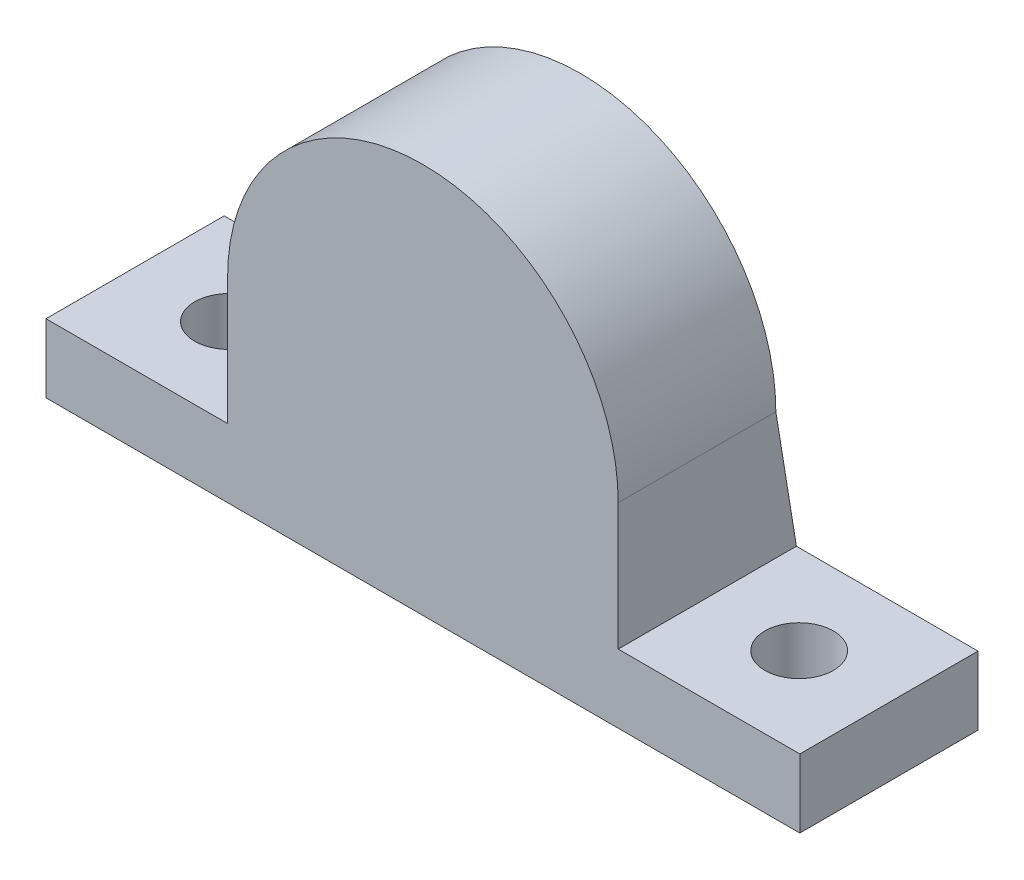
SolidWorks part; units mm, degrees
ref_plane "Alzado" through (0, 0, 0) normal (0, 0, 1) x (1, 0, 0)
ref_plane "Planta" through (0, 0, 0) normal (0, 1, 0) x (1, 0, 0)
ref_plane "Vista lateral" through (0, 0, 0) normal (1, 0, 0) x (0, 0, -1)
sketch "Croquis1" plane through (0, 0, 0) normal (0, 1, 0) x (1, 0, 0)
  line L1 (-27.5, 6.5) -> (27.5, 6.5)
  line L2 (-27.5, 6.5) -> (-27.5, -6.5)
  line L3 (-27.5, -6.5) -> (27.5, -6.5)
  line L4 (27.5, 6.5) -> (27.5, -6.5)
  line L5 (-27.5, 6.5) -> (27.5, -6.5) construction
  line L6 (-27.5, -6.5) -> (27.5, 6.5) construction
  point P0 (0, 0)
extrude "Saliente-Extruir1" add sketch "Croquis1" along normal blind 5
sketch "Croquis2" plane through (0, 5, 0) normal (0, 1, 0) x (1, 0, 0)
  circle A0 centre (-20.65, 0) radius 2.5
  circle A1 centre (20.95, 0) radius 2.5
  dimension "D1" = 41.6
  dimension "D2" = 20.65
extrude "Cortar-Extruir1" cut sketch "Croquis2" against normal blind 5
sketch "Croquis3" plane through (0, 5, 0) normal (0, 1, 0) x (1, 0, 0)
  line L0 (27.5, 6.5) -> (-27.5, 6.5) construction
  line L1 (-13, 6.5) -> (13, 6.5)
  line L2 (-13, 6.5) -> (-13, 1.5)
  line L3 (-13, 1.5) -> (13, 1.5)
  line L4 (13, 6.5) -> (13, 1.5)
  line L5 (-27.5, -6.5) -> (27.5, -6.5) construction
  line L6 (-13, -6.5) -> (13, -6.5)
  line L7 (-13, -6.5) -> (-13, -1.5)
  line L8 (-13, -1.5) -> (13, -1.5)
  line L9 (13, -6.5) -> (13, -1.5)
  line L10 (-27.5, 6.5) -> (-27.5, -6.5) construction
  line L11 (27.5, -6.5) -> (27.5, 6.5) construction
  point P15 (13, 4)
  dimension "D1" = 1.5
  dimension "D2" = 3
  dimension "D3" = 14.5
  dimension "D4" = 14.5
  dimension "D5" = 14.5
  dimension "D6" = 14.5
extrude "Cortar-Extruir2" cut sketch "Croquis3" against normal blind 5
sketch "Croquis4" plane through (0, 0, 1.5) normal (0, 0, 1) x (1, 0, 0)
  line L0 (13, 0) -> (-13, 0) construction
  circle A0 centre (0, 14.25) radius 14.25
  dimension "D1" = 14.25
extrude "Saliente-Extruir2" add sketch "Croquis4" against normal blind 8 and the other way blind 5
sketch "Croquis5" plane through (0, 0, -6.5) normal (0, 0, -1) x (-1, 0, 0)
  circle A0 centre (0, 14.25) radius 12
  circle A1 centre (0, 14.25) radius 14.25 construction
  dimension "D1" = 0
extrude "Cortar-Extruir3" cut sketch "Croquis5" against normal blind 1
sketch "Croquis6" plane through (0, 0, 6.5) normal (0, 0, 1) x (1, 0, 0)
  circle A0 centre (0, 14.25) radius 12
  circle A1 centre (0, 14.25) radius 14.25 construction
  dimension "D1" = 0
extrude "Cortar-Extruir4" cut sketch "Croquis6" against normal blind 1
sketch "Croquis7" plane through (0, 0, 5.5) normal (0, 0, 1) x (1, 0, 0)
  line L0 (-12, 14.25) -> (-13, 0)
  line L1 (-14.25, 14.25) -> (-14.25, 5)
  line L2 (-27.5, 5) -> (-13, 5) construction
  line L3 (-14.25, 5) -> (-13, 0)
  line L4 (-12, 14.25) -> (-14.25, 14.25)
  line L5 (12, 14.25) -> (13, 0)
  line L6 (12, 14.25) -> (14.25, 14.25)
  line L7 (14.25, 14.25) -> (14.25, 5)
  line L8 (13, 5) -> (27.5, 5) construction
  line L9 (14.25, 5) -> (13, 0)
  circle A1 centre (0, 14.25) radius 12 construction
  circle A2 centre (0, 14.25) radius 12 construction
  circle A3 centre (0, 14.25) radius 14.25 construction
extrude "Saliente-Extruir3" add sketch "Croquis7" against normal blind 12 and the other way blind 1
sketch "Croquis8" plane through (0, 0, 6.5) normal (0, 0, 1) x (1, 0, 0)
  line L0 (-10.8397, 5) -> (-13.1837, 5)
  line L1 (-13.1837, 5) -> (-12.6491, 8.4632)
  line L2 (-12.6491, 8.4632) -> (-10.8397, 5)
  line L3 (12.7285, 8.4632) -> (12.6491, 5)
  line L4 (12.6491, 5) -> (10.8397, 5)
  line L5 (12.6491, 5) -> (10.8397, 5) construction
  line L6 (10.8397, 5) -> (12.7285, 8.4632)
  arc A0 (-12.4824, 7.376) -> (12.4824, 7.376) centre (0, 14.25) ccw construction
extrude "Saliente-Extruir4" add sketch "Croquis8" against normal blind 13
sketch "Croquis9" plane through (0, 0, 5.5) normal (0, 0, 1) x (1, 0, 0)
  circle A0 centre (0, 14.25) radius 11
  circle A1 centre (0, 14.25) radius 12 construction
  dimension "D1" = 0
extrude "Cortar-Extruir5" cut sketch "Croquis9" against normal blind 13
sketch "Croquis10" plane through (0, 0, -6.5) normal (0, 0, -1) x (-1, 0, 0)
  line L1 (-14.25, 14.25) -> (16.3046, 14.25)
  line L2 (-14.25, 14.25) -> (-14.25, 31.975)
  line L3 (-14.25, 31.975) -> (16.3046, 31.975)
  line L4 (16.3046, 14.25) -> (16.3046, 31.975)
extrude "Cortar-Extruir6" cut sketch "Croquis10" against normal blind 1.5
sketch "Croquis11" plane through (0, 0, 6.5) normal (0, 0, 1) x (1, 0, 0)
  line L1 (14.25, 14.25) -> (-17.3775, 14.25)
  line L2 (14.25, 14.25) -> (14.25, 32.8108)
  line L3 (14.25, 32.8108) -> (-17.3775, 32.8108)
  line L4 (-17.3775, 14.25) -> (-17.3775, 32.8108)
extrude "Cortar-Extruir7" cut sketch "Croquis11" against normal blind 1.5
sketch "Croquis13" plane through (0, 0, 5) normal (0, 0, 1) x (1, 0, 0)
  circle A0 centre (0, 14.25) radius 12
extrude "Cortar-Extruir8" cut sketch "Croquis13" against normal blind 1.5
sketch "Croquis14" plane through (0, 0, -5) normal (0, 0, -1) x (-1, 0, 0)
  circle A0 centre (0, 14.25) radius 12
extrude "Cortar-Extruir10" cut sketch "Croquis14" against normal blind 1.5
sketch "Croquis15" plane through (0, 0, -3.5) normal (0, 0, -1) x (-1, 0, 0)
  circle A0 centre (0, 14.25) radius 12
extrude "Cortar-Extruir11" cut sketch "Croquis15" along normal blind 5
sketch "Croquis16" plane through (0, 0, 3.5) normal (0, 0, 1) x (1, 0, 0)
  circle A0 centre (0, 14.25) radius 12
extrude "Cortar-Extruir12" cut sketch "Croquis16" along normal blind 5
sketch "Croquis17" plane through (0, 0, 5) normal (0, 0, 1) x (1, 0, 0)
  line L0 (-12, 14.25) -> (-13, 0)
  line L1 (-13, 0) -> (13, 0)
  line L2 (13, 0) -> (12, 14.25)
  line L3 (12, 14.25) -> (-12, 14.25)
  circle A0 centre (0, 14.25) radius 12 construction
  arc A1 (12, 14.25) -> (-12, 14.25) centre (0, 14.25) ccw construction
extrude "Cortar-Extruir13" cut sketch "Croquis17" along normal blind 20
sketch "Croquis18" plane through (-14.25, 0, 0) normal (-1, 0, 0) x (0, 0, 1)
  line L0 (5, 14.25) -> (6.5, 5)
  line L1 (6.5, 5) -> (6.5, 14.25)
  line L2 (6.5, 14.25) -> (5, 14.25)
extrude "Cortar-Extruir14" cut sketch "Croquis18" against normal blind 36
sketch "Croquis19" plane through (14.25, 0, 0) normal (1, 0, 0) x (0, 0, -1)
  line L0 (5, 14.25) -> (6.5, 5)
  line L1 (6.5, 5) -> (6.5, 14.25)
  line L2 (6.5, 14.25) -> (5, 14.25)
extrude "Cortar-Extruir15" cut sketch "Croquis19" against normal blind 36
sketch "Croquis20" plane through (0, 0, -5) normal (0, 0, -1) x (-1, 0, 0)
  line L0 (-12, 14.25) -> (-13, 0)
  line L1 (-13, 0) -> (13, 0)
  line L2 (13, 0) -> (12, 14.25)
  line L3 (12, 14.25) -> (-12, 14.25)
  circle A0 centre (0, 14.25) radius 12 construction
  arc A1 (7.6444, 5) -> (12, 14.25) centre (0, 14.25) ccw construction
extrude "Cortar-Extruir16" cut sketch "Croquis20" along normal blind 23
sketch "Croquis22" plane through (0, 0, 3.5) normal (0, 0, 1) x (1, 0, 0)
  circle A0 centre (0, 14.25) radius 12
extrude "Saliente-Extruir6" add sketch "Croquis22" along normal blind 1.5
sketch "Croquis23" plane through (0, 0, 5) normal (0, 0, 1) x (1, 0, 0)
  circle A0 centre (0, 14.25) radius 14.25
extrude "Saliente-Extruir7" add sketch "Croquis23" along normal blind 1.5
sketch "Croquis24" plane through (0, 0, 1.5) normal (0, 0, 1) x (1, 0, 0)
  line L0 (-13, 0) -> (-12.4824, 7.376)
  line L1 (-13, 0) -> (0, 0)
  circle A0 centre (0, 14.25) radius 14.25
  line M1 (-12.6491, 5) -> (-13, 0)
  line M2 (-13, 0) -> (0, 0)
  arc M3 (0, 0) -> (-10.8397, 5) centre (0, 14.25) cw
  line M4 (-10.8397, 5) -> (-12.6491, 5)
extrude "Saliente-Extruir9" add sketch "Croquis24" along normal up to vertex (5 mm away) contours M4 M1 M2 M3
sketch "Croquis26" plane through (0, 0, 1.5) normal (0, 0, 1) x (1, 0, 0)
  line L0 (12.6491, 5) -> (10.8397, 5)
  line L1 (13, 0) -> (0, 0)
  line L2 (13, 0) -> (12.6491, 5)
  circle A0 centre (0, 14.25) radius 14.25
  line M1 (13, 0) -> (12.6491, 5)
  line M2 (12.6491, 5) -> (10.8397, 5)
  arc M3 (10.8397, 5) -> (0, 0) centre (0, 14.25) cw
  line M4 (0, 0) -> (13, 0)
extrude "Saliente-Extruir10" add sketch "Croquis26" along normal up to vertex (5 mm away) contours M4 M1 M2 M3
sketch "Croquis27" plane through (0, 0, 6.5) normal (0, 0, 1) x (1, 0, 0)
  line L0 (-10.8397, 5) -> (-14.25, 5)
  line L1 (-14.25, 5) -> (-14.25, 14.25)
  circle A0 centre (0, 14.25) radius 14.25
  arc M4 (10.8397, 5) -> (-10.8397, 5) centre (0, 14.25) ccw
  line M5 (-10.8397, 5) -> (-12.6491, 5)
  line M6 (-12.6491, 5) -> (-14.25, 5)
extrude "Saliente-Extruir11" add sketch "Croquis27" against normal blind 1.5 contours L1 M6 M5 M4
sketch "Croquis28" plane through (0, 0, 6.5) normal (0, 0, 1) x (1, 0, 0)
  line L0 (10.8397, 5) -> (14.25, 5)
  line L1 (14.25, 5) -> (14.25, 14.25)
  circle A0 centre (0, 14.25) radius 14.25
  line M7 (14.25, 5) -> (12.6491, 5)
  line M8 (12.6491, 5) -> (10.8397, 5)
  arc M9 (10.8397, 5) -> (-14.25, 14.25) centre (0, 14.25) ccw
extrude "Saliente-Extruir12" add sketch "Croquis28" against normal blind 1.5 contours L1 M7 M9 M8
sketch "Croquis30" plane through (0, 0, -3.5) normal (0, 0, -1) x (-1, 0, 0)
  circle A0 centre (0, 14.25) radius 11.125
  circle A1 centre (0, 14.25) radius 11
extrude "Saliente-Extruir13" add sketch "Croquis30" against normal blind 10
sketch "Croquis31" plane through (0, 0, -3.5) normal (0, 0, -1) x (-1, 0, 0)
  circle A0 centre (0, 14.25) radius 11.125
extrude "Cortar-Extruir17" cut sketch "Croquis31" against normal up to surface (7 mm away) up to face at (11, 14.25, 3.5)
sketch "Croquis32" plane through (0, 0, -3.5) normal (0, 0, -1) x (-1, 0, 0)
  circle A0 centre (0, 14.25) radius 11.25
extrude "Cortar-Extruir18" cut sketch "Croquis32" against normal up to surface (7 mm away)
